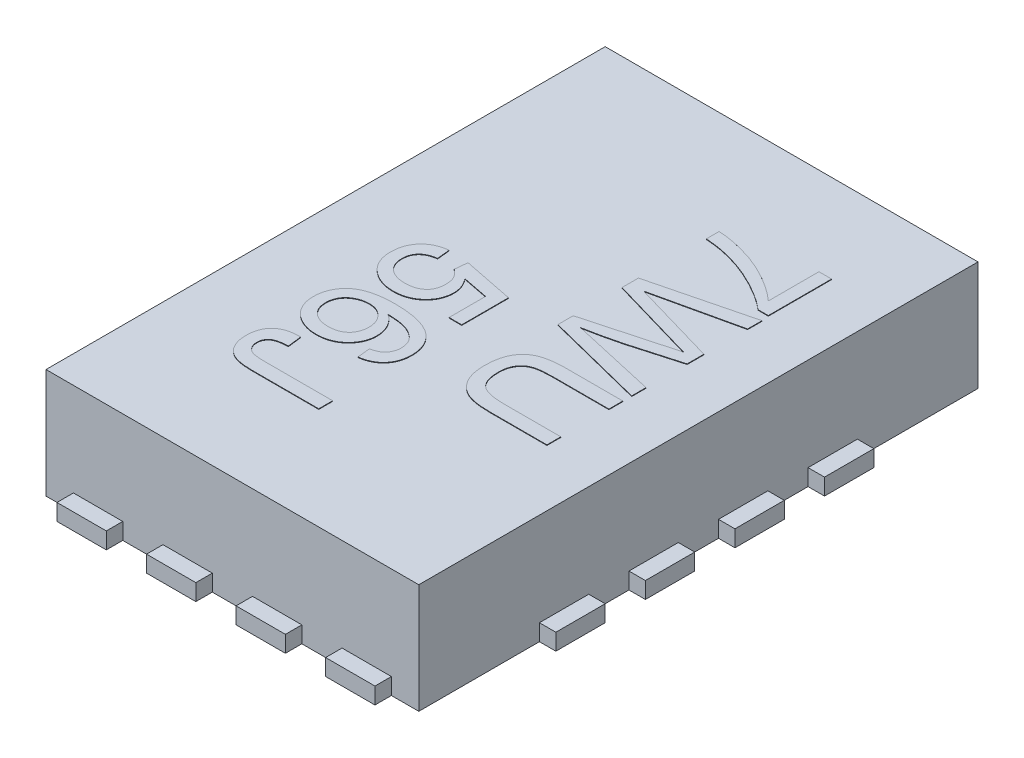
SolidWorks part; units mm, degrees
ref_plane "Front Plane" through (0, 0, 0) normal (0, 0, 1) x (1, 0, 0)
ref_plane "Top Plane" through (0, 0, 0) normal (0, 1, 0) x (1, 0, 0)
ref_plane "Right Plane" through (0, 0, 0) normal (1, 0, 0) x (0, 0, -1)
sketch "Sketch1" plane through (0, 0, 0) normal (0, 1, 0) x (1, 0, 0)
  line L1 (-0.8636, 1.2954) -> (0.8636, 1.2954)
  line L2 (-0.8636, 1.2954) -> (-0.8636, -1.2954)
  line L3 (-0.8636, -1.2954) -> (0.8636, -1.2954)
  line L4 (0.8636, 1.2954) -> (0.8636, -1.2954)
  point P4 (0.8636, 0)
  point P6 (0, 1.2954)
  dimension "D1" = 1.7272
  dimension "D2" = 2.5908
extrude "Boss-Extrude1" add sketch "Sketch1" along normal blind 0.508
sketch "Sketch2" plane through (0, 0, 1.2954) normal (0, 0, 1) x (1, 0, 0)
  line L0 (-0.3217, 0.0762) -> (-0.508, 0.0762) construction
  line L1 (-0.7366, 0.0762) -> (-0.508, 0.0762)
  line L2 (-0.7366, 0.0762) -> (-0.7366, 0)
  line L3 (-0.7366, 0) -> (-0.508, 0)
  line L4 (-0.508, 0.0762) -> (-0.508, 0)
  line L5 (-0.3217, 0.0762) -> (-0.0931, 0.0762)
  line L6 (-0.3217, 0.0762) -> (-0.3217, 0)
  line L7 (-0.3217, 0) -> (-0.0931, 0)
  line L8 (-0.0931, 0.0762) -> (-0.0931, 0)
  line L9 (0.0931, 0.0762) -> (0.3217, 0.0762)
  line L10 (0.0931, 0.0762) -> (0.0931, 0)
  line L11 (0.0931, 0) -> (0.3217, 0)
  line L12 (0.3217, 0.0762) -> (0.3217, 0)
  line L13 (0.508, 0.0762) -> (0.7366, 0.0762)
  line L14 (0.508, 0.0762) -> (0.508, 0)
  line L15 (0.508, 0) -> (0.7366, 0)
  line L16 (0.7366, 0.0762) -> (0.7366, 0)
  line L17 (-0.0931, 0.0762) -> (0.0931, 0.0762) construction
  line L18 (0.3217, 0.0762) -> (0.508, 0.0762) construction
  line L19 (-0.8636, 0) -> (0.8636, 0) construction
  line L20 (-0.8636, 0.508) -> (-0.8636, 0) construction
  point P18 (0, 0.0762)
  point P19 (0, 0)
  dimension "D1" = 0.2286
  dimension "D2" = 0.127
  dimension "D3" = 0.0762
sketch "Sketch4" plane through (0.8636, 0, 0) normal (1, 0, 0) x (0, 0, -1)
  line L0 (-0.508, 0.0762) -> (-0.3217, 0.0762) construction
  line L1 (-0.3217, 0.0762) -> (-0.0931, 0.0762)
  line L2 (-0.3217, 0.0762) -> (-0.3217, 0)
  line L3 (-0.3217, 0) -> (-0.0931, 0)
  line L4 (-0.0931, 0.0762) -> (-0.0931, 0)
  line L5 (0.0931, 0) -> (0.3217, 0)
  line L6 (0.0931, 0) -> (0.0931, 0.0762)
  line L7 (0.0931, 0.0762) -> (0.3217, 0.0762)
  line L8 (0.3217, 0) -> (0.3217, 0.0762)
  line L9 (0.7366, 0.0762) -> (0.508, 0.0762)
  line L10 (0.7366, 0.0762) -> (0.7366, 0)
  line L11 (0.7366, 0) -> (0.508, 0)
  line L12 (0.508, 0.0762) -> (0.508, 0)
  line L13 (-0.508, 0.0762) -> (-0.7366, 0.0762)
  line L14 (-0.508, 0.0762) -> (-0.508, 0)
  line L15 (-0.508, 0) -> (-0.7366, 0)
  line L16 (-0.7366, 0.0762) -> (-0.7366, 0)
  line L17 (-0.0931, 0.0762) -> (0.0931, 0.0762) construction
  line L18 (0.3217, 0.0762) -> (0.508, 0.0762) construction
  line L19 (-1.2954, 0) -> (1.2954, 0) construction
  point P16 (0, 0.0762)
  point P19 (0, 0)
  dimension "D1" = 0.2286
  dimension "D2" = 0.1863
extrude "Boss-Extrude3" add sketch "Sketch2" along normal blind 0.0762
extrude "Boss-Extrude4" add sketch "Sketch4" along normal blind 0.0762
mirror "Mirror1" about plane through (0, 0, 0) normal (0, 0, 1) of "Boss-Extrude3"
mirror "Mirror2" about plane through (0, 0, 0) normal (1, 0, 0) of "Boss-Extrude4"
sketch "Sketch5" plane through (0, 0.508, 0) normal (0, 1, 0) x (1, 0, 0)
  line L0 (0.1444, -1.1238) -> (0.1444, 0.9142) construction
  line L1 (-0.5288, 1.0832) -> (-0.5288, -0.8764) construction
  text T0 "7WU" height 0.4572
  text T1 "56J" height 0.4572
  point P5 (0.1444, 0.9142)
  point P6 (0.0808, 0.9672)
  point P7 (-0.5246, -0.6599)
  point P8 (-0.5288, -0.8764)
extrude "Boss-Extrude5" add sketch "Sketch5" along normal blind 0.0025
